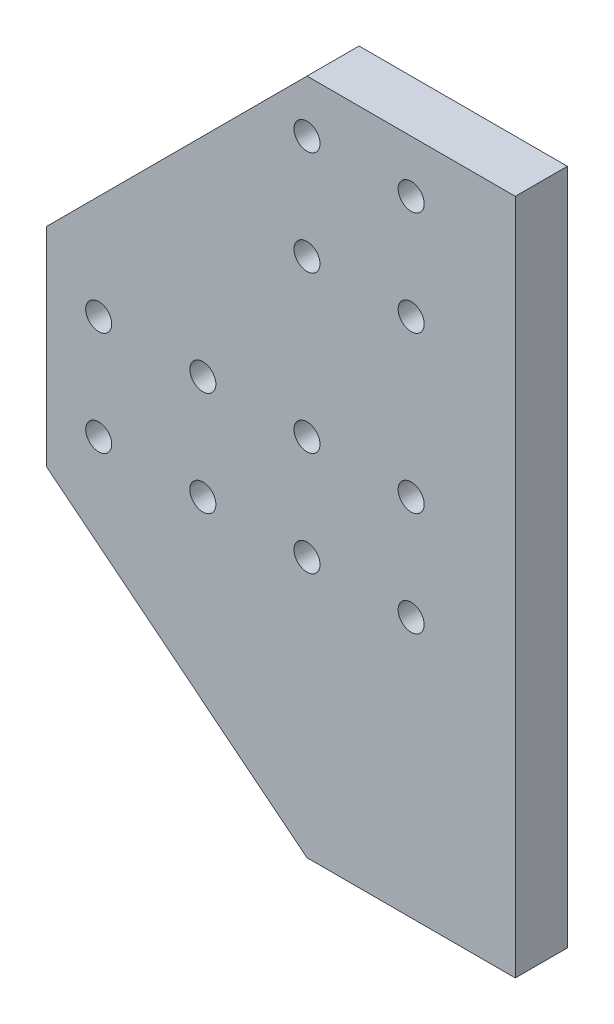
SolidWorks part; units mm, degrees
ref_plane "Front Plane" through (0, 0, 0) normal (0, 0, 1) x (1, 0, 0)
ref_plane "Top Plane" through (0, 0, 0) normal (0, 1, 0) x (1, 0, 0)
ref_plane "Right Plane" through (0, 0, 0) normal (1, 0, 0) x (0, 0, -1)
sketch "Sketch1" plane through (0, 0, 0) normal (0, 0, 1) x (1, 0, 0)
  line L0 (0, 0) -> (40, 0)
  line L1 (40, 0) -> (40, 130)
  line L2 (40, 130) -> (0, 130)
  line L3 (0, 130) -> (-50, 80)
  line L4 (-50, 80) -> (-50, 40)
  line L5 (-50, 40) -> (0, 0)
  dimension "D1" = 130
  dimension "D2" = 40
  dimension "D3" = 40
  dimension "D4" = 40
  dimension "D5" = 90
  dimension "D6" = 50
extrude "Boss-Extrude1" add sketch "Sketch1" along normal blind 10
sketch "Sketch2" plane through (0, 0, 10) normal (0, 0, 1) x (1, 0, 0)
  line L0 (40, 130) -> (0, 130) construction
  line L1 (40, 0) -> (40, 130) construction
  circle A0 centre (0, 120) radius 2.5
  circle A1 centre (20, 120) radius 2.5
  circle A2 centre (0, 100) radius 2.5
  circle A3 centre (20, 100) radius 2.5
  circle A4 centre (-40, 70) radius 2.5
  circle A5 centre (-20, 70) radius 2.5
  circle A6 centre (-40, 50) radius 2.5
  circle A7 centre (-20, 50) radius 2.5
  circle A8 centre (0, 70) radius 2.5
  circle A9 centre (20, 70) radius 2.5
  circle A10 centre (0, 50) radius 2.5
  circle A11 centre (20, 50) radius 2.5
  point P24 (0, 0)
  point P25 (0, 0)
  point P26 (0, 0)
  point P27 (0, 0)
  point P28 (0, 0)
  point P29 (0, 0)
  point P30 (0, 0)
  point P31 (0, 0)
  point P32 (0, 0)
  point P33 (0, 0)
  point P34 (0, 0)
  point P37 (0, 0)
  point P38 (0, 0)
  point P39 (-19.1767, 49.1152)
  point P42 (-20, 49.6276)
  point P43 (0, 0)
  dimension "D1" = 5
  dimension "D6" = 20
  dimension "D2" = 10
  dimension "D3" = 20
  dimension "D4" = 30
  dimension "D5" = 20
  dimension "D7" = 20
  dimension "D8" = 20
  dimension "D9" = 20
extrude "Cut-Extrude1" cut sketch "Sketch2" against normal blind 10
